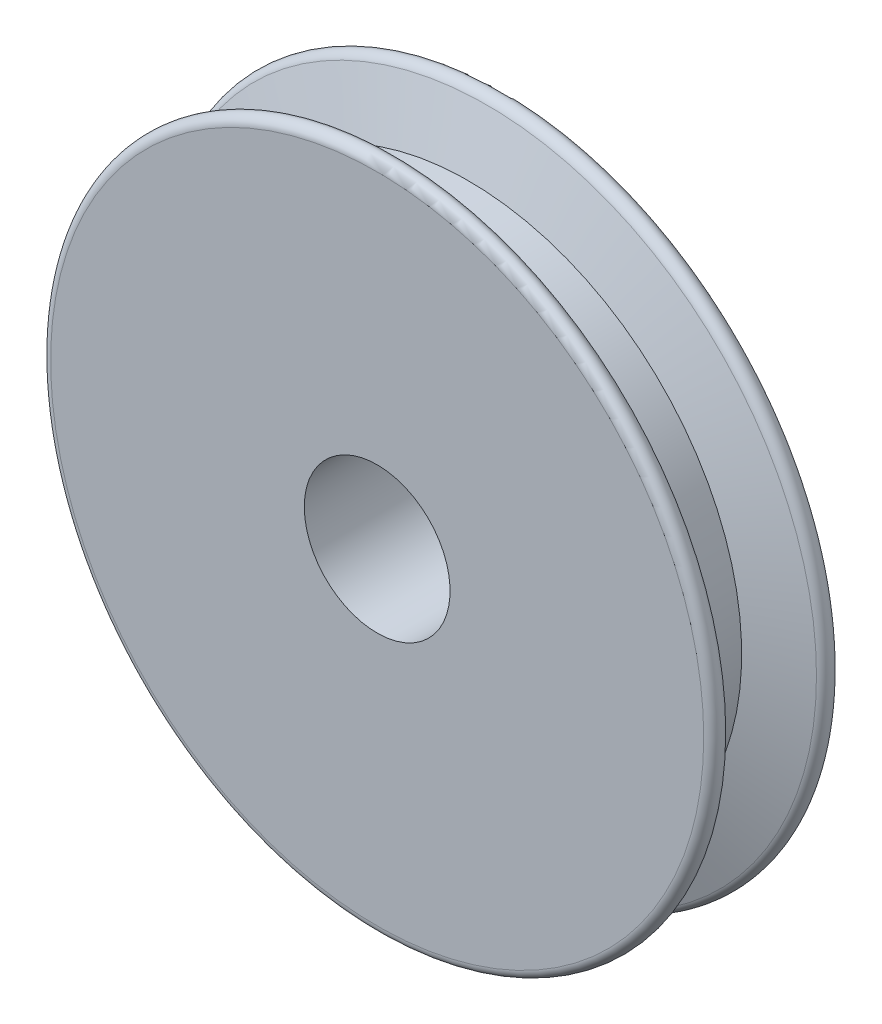
SolidWorks part; units mm, degrees
ref_plane "Front Plane" through (0, 0, 0) normal (1, 0, 0) x (0, 1, 0)
ref_plane "Top Plane" through (0, 0, 0) normal (0, 0, 1) x (0, 1, 0)
ref_plane "Right Plane" through (0, 0, 0) normal (0, 1, 0) x (-1, 0, 0)
sketch "Sketch1" plane through (0, 0, 0) normal (1, 0, 0) x (0, 1, 0)
  line L0 (10.16, 0) -> (10.16, 17.78)
  line L1 (55, 0) -> (-55, 0) construction
  line L2 (10.16, 17.78) -> (53.34, 17.78)
  line L3 (53.34, 17.78) -> (38.1, 12.7)
  line L4 (10.16, 0) -> (53.357, 0)
  line L5 (53.357, 0) -> (38.1, 5.08)
  line L6 (38.1, 5.08) -> (38.1, 12.7)
  line L7 (0, -55) -> (0, 55) construction
  point P11 (0, 0)
  point P12 (0, 0)
  dimension "D1" = 10.16
  dimension "D2" = 43.18
  dimension "D3" = 7.62
  dimension "D4" = 5.08
  dimension "D5" = 5.08
  dimension "D6" = 17.78
  dimension "D7" = 27.94
sketch "Sketch2" plane through (0, 0, 0) normal (0, 1, 0) x (-1, 0, 0)
  line L0 (0, 0) -> (0, 9.8421) construction
revolve "Revolve1" add sketch "Sketch1" angle 360 about L0
fillet "Fillet2" radius 1.27 2 edges at (-53.357, 0, 0) (-53.34, 0, 17.78)
equation "\"D5@Sketch1\"=\"D4@SKETCH1\""
